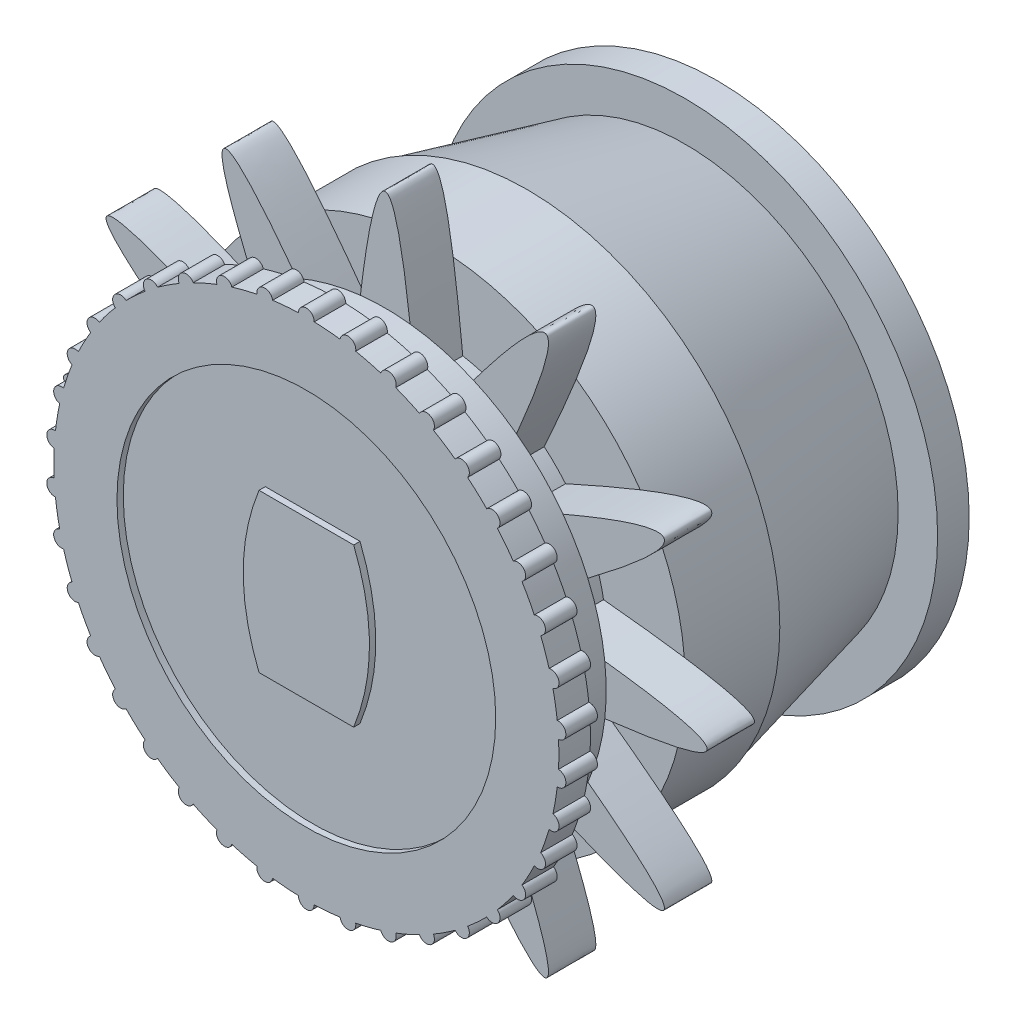
SolidWorks part; units mm, degrees
ref_plane "Front Plane" through (0, 0, 0) normal (0, 0, 1) x (1, 0, 0)
ref_plane "Top Plane" through (0, 0, 0) normal (0, 1, 0) x (1, 0, 0)
ref_plane "Right Plane" through (0, 0, 0) normal (1, 0, 0) x (0, 0, -1)
sketch "Sketch1" plane through (0, 0, 0) normal (0, 0, 1) x (1, 0, 0)
  circle A0 centre (0, 0) radius 5.5
  dimension "GearPlate" = 11
extrude "GearPlate" add sketch "Sketch1" along normal blind 1.5
sketch "Sketch2" plane through (0, 0, 1.5) normal (0, 0, 1) x (1, 0, 0)
  line L0 (0, 0) -> (0, 10.2) construction
  line L1 (0, 5.5) -> (0, 10.1138) construction
  line L2 (-0.9565, 10.1976) -> (0.9565, 10.1976) construction
  line L3 (-0.9565, 10.1976) -> (-0.9565, 5.4162) construction
  line L4 (-0.9565, 5.4162) -> (0.9565, 5.4162) construction
  line L5 (0.9565, 10.1976) -> (0.9565, 5.4162) construction
  line L6 (-0.9565, 10.1976) -> (0.9565, 5.4162) construction
  line L7 (-0.9565, 5.4162) -> (0.9565, 10.1976) construction
  line L10 (-0.9565, 5.4162) -> (0.9565, 5.4162)
  circle A0 centre (0, 0) radius 5.5 construction
  spline S0 degree 2 poles (-0.9565, 5.4162) (0, 14.9791) (0.9565, 5.4162) knots 0 0 0 1 1 1
  point P0 (0, 7.8069)
  point P7 (0, 7.8069)
  point P11 (-0.7667, 10.1976)
  point P12 (0.2333, 10.1976)
  dimension "D1" = 10.2
extrude "Boss-Extrude3" add sketch "Sketch2" against normal blind 1.5
pattern_circular "CirPattern2" count 12 over 360 about axis through (0, 0, 1.5) along (0, 0, -1) of "Boss-Extrude3"
sketch "Sketch3" plane through (0, 0, 1.5) normal (0, 0, 1) x (1, 0, 0)
  circle A0 centre (0, 0) radius 7
  dimension "Plate" = 14
extrude "Plate" add sketch "Sketch3" along normal blind 1.5
sketch "Sketch4" plane through (0, 0, 3) normal (0, 0, 1) x (1, 0, 0)
  circle A0 centre (0, 0) radius 8
  dimension "SmallGearPlate" = 16
extrude "SmallGearPlate" add sketch "Sketch4" along normal blind 1
sketch "Sketch6" plane through (0, 0, 4) normal (0, 0, 1) x (1, 0, 0)
  line L0 (0, 0) -> (0, 10.621) construction
  circle A0 centre (0, 8) radius 0.25
  circle A1 centre (0, 0) radius 8 construction
  dimension "D1" = 0.5
extrude "Boss-Extrude7" add sketch "Sketch6" against normal blind 1
pattern_circular "CirPattern3" count 38 over 360 about axis through (0, 0, 0) along (0, 0, 1) of "Boss-Extrude7"
sketch "Sketch7" plane through (0, 0, 4) normal (0, 0, 1) x (1, 0, 0)
  circle A0 centre (0, 0) radius 6
  dimension "SmallGearCut" = 12
extrude "SmallGearCut" cut sketch "Sketch7" against normal blind 0.2
sketch "Sketch8" plane through (0, 0, 3.8) normal (0, 0, 1) x (1, 0, 0)
  line L0 (-1.5, -2.5) -> (1.5, -2.5)
  line L8 (2, 2) -> (2.0184, 1.9675) construction
  line L11 (-1.5, 2.5) -> (1.5, 2.5)
  spline S0 degree 2 poles (-1.5, 2.5) (-2.5, 0) (-1.5, -2.5) knots 0 0 0 1 1 1
  spline S2 degree 2 poles (1.5, 2.5) (2.5, 0) (1.5, -2.5) knots 0 0 0 1 1 1
  point P0 (0, 0)
  point P10 (-1.5, 2.5)
  point P11 (1.5, 2.5)
  point P12 (-1.5, -2.5)
  point P13 (1.5, -2.5)
  point P14 (-6.1413, 10.3588)
extrude "Boss-Extrude9" add sketch "Sketch8" along normal blind 0.2
sketch "Sketch10" plane through (0, 0, 0) normal (0, 0, -1) x (-1, 0, 0)
  circle A0 centre (0, 0) radius 8
  dimension "D1" = 16
extrude "BackPlate" add sketch "Sketch10" along normal blind 3
ref_plane "Plane1" through (0, 0, -8) normal (0, 0, -1) x (-1, 0, 0)
sketch "Sketch11" plane through (0, 0, -8) normal (0, 0, -1) x (-1, 0, 0)
  circle A0 centre (0, 0) radius 6.75
  dimension "D1" = 13.5
extrude "Boss-Extrude11" add sketch "Sketch11" against normal up to surface (5 mm away) draft 13.7
sketch "Sketch12" plane through (0, 0, -8) normal (0, 0, -1) x (-1, 0, 0)
  circle A0 centre (0, 0) radius 8
  dimension "D1" = 16
extrude "Boss-Extrude12" add sketch "Sketch12" along normal blind 1
